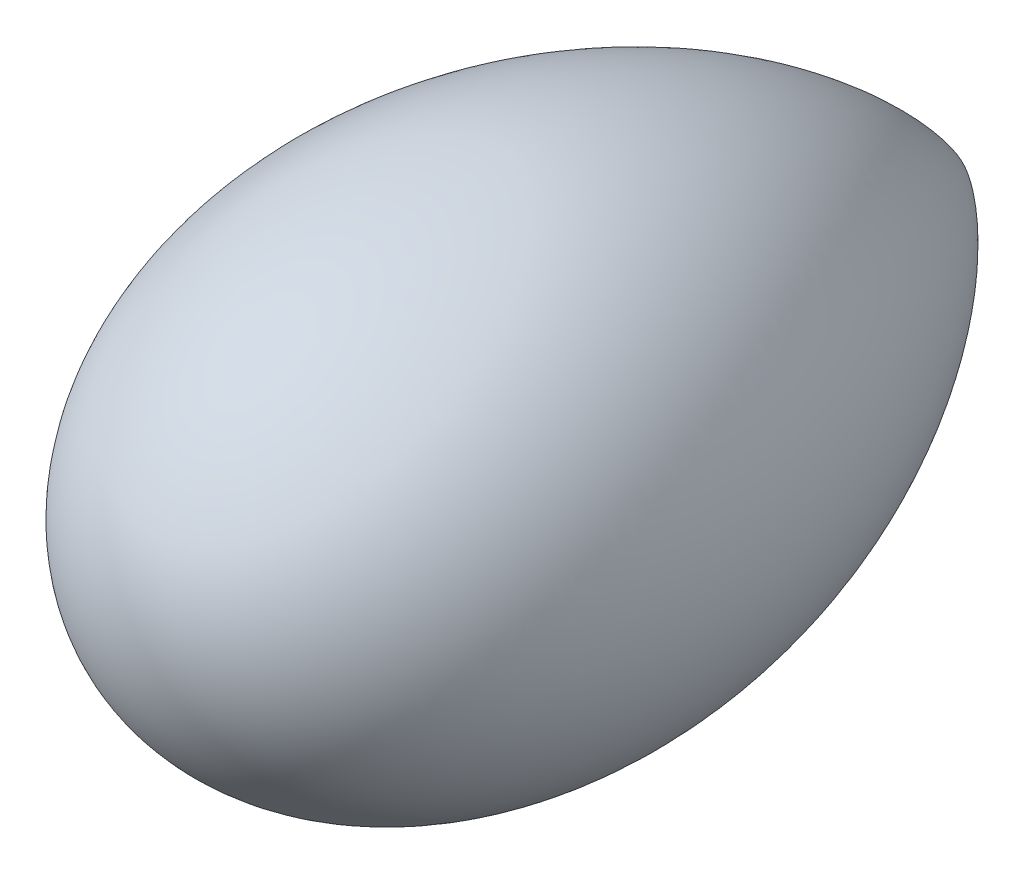
SolidWorks part; units mm, degrees
ref_plane "Front Plane" through (0, 0, 0) normal (0, 0, 1) x (1, 0, 0)
ref_plane "Top Plane" through (0, 0, 0) normal (0, 1, 0) x (1, 0, 0)
ref_plane "Right Plane" through (0, 0, 0) normal (1, 0, 0) x (0, 0, -1)
sketch "Sketch1" plane through (0, 0, 0) normal (0, 1, 0) x (1, 0, 0)
  line L0 (0, 0) -> (0, -55.7313) construction
  line L1 (0, -111.4626) -> (0, 0)
  spline S0 degree 4 poles (-12.5087, -108.2668) (-12.266, -108.3959) (-11.7775, -108.648) (-11.035, -109.0075) (-10.0274, -109.4481) (-9.0074, -109.8468) (-7.977, -110.2028) (-6.9374, -110.5156) (-5.8912, -110.7847) (-4.9658, -110.9822) (-4.169, -111.124) (-3.4992, -111.2236) (-2.9671, -111.292) (-2.4225, -111.3491) (-1.8981, -111.3948) (-1.3334, -111.4292) (-0.841, -111.4521) (-0.2181, -111.4635) (0.2032, -111.4636) (0.8134, -111.4527) (1.292, -111.4312) (1.7718, -111.403) (2.1542, -111.3721) (2.5474, -111.3359) (2.9371, -111.2944) (3.3917, -111.2382) (4.0392, -111.1447) (4.8129, -111.0116) (5.7099, -110.826) (6.9798, -110.5099) (8.482, -110.0508) (9.9521, -109.4954) (11.6226, -108.7419) (13.2441, -107.8883) (14.8128, -106.9401) (16.5278, -105.7371) (18.1608, -104.4253) (19.7092, -103.0148) (21.1713, -101.5153) (22.5463, -99.9356) (24.1563, -97.8715) (25.7407, -95.5252) (27.2623, -92.8896) (28.5916, -90.1533) (29.5695, -87.833) (30.5488, -85.1788) (31.4833, -82.1794) (32.3589, -78.6193) (33.259, -73.4603) (33.8043, -67.1946) (33.7131, -59.8531) (32.692, -51.5269) (30.8192, -43.3516) (28.1468, -35.4025) (24.7149, -27.7508) (21.072, -21.3806) (17.5018, -16.2063) (14.2272, -12.121) (11.7755, -9.3964) (9.557, -7.1726) (7.7692, -5.5355) (6.4734, -4.4233) (5.038, -3.2639) (3.8281, -2.3573) (2.7009, -1.5761) (1.6613, -0.9177) (1.0906, -0.5771) (0.5935, -0.299) (0.2568, -0.1232) (0.086, -0.0402) (0, 0) knots 0 0 0 0 0 0.007194 0.014388 0.021582 0.028776 0.035845 0.042913 0.049982 0.05705 0.060585 0.064119 0.067653 0.071188 0.074722 0.078256 0.08179 0.085325 0.088749 0.092172 0.095596 0.09902 0.100732 0.102444 0.105868 0.109292 0.112716 0.119563 0.126411 0.133259 0.146955 0.16065 0.167498 0.181193 0.194889 0.208584 0.22228 0.235976 0.249671 0.263367 0.277062 0.304453 0.323693 0.342933 0.356628 0.370324 0.397715 0.425106 0.452497 0.507279 0.562062 0.616844 0.671626 0.726408 0.78119 0.835973 0.863364 0.890755 0.918146 0.931841 0.945537 0.954184 0.96283 0.980124 0.985093 0.990062 0.995031 0.997515 1 1 1 1 1 construction
  spline S1 degree 4 poles (0, -111.4626) (0.1197, -111.4626) (0.3594, -111.4608) (0.8134, -111.4527) (1.292, -111.4312) (1.7718, -111.403) (2.1542, -111.3721) (2.5474, -111.3359) (2.9371, -111.2944) (3.3917, -111.2382) (4.0392, -111.1447) (4.8129, -111.0116) (5.7099, -110.826) (6.9798, -110.5099) (8.482, -110.0508) (9.9521, -109.4954) (11.6226, -108.7419) (13.2441, -107.8883) (14.8128, -106.9401) (16.5278, -105.7371) (18.1608, -104.4253) (19.7092, -103.0148) (21.1713, -101.5153) (22.5463, -99.9356) (24.1563, -97.8715) (25.7407, -95.5252) (27.2623, -92.8896) (28.5916, -90.1533) (29.5695, -87.833) (30.5488, -85.1788) (31.4833, -82.1794) (32.3589, -78.6193) (33.259, -73.4603) (33.8043, -67.1946) (33.7131, -59.8531) (32.692, -51.5269) (30.8192, -43.3516) (28.1468, -35.4025) (24.7149, -27.7508) (21.072, -21.3806) (17.5018, -16.2063) (14.2272, -12.121) (11.7755, -9.3964) (9.557, -7.1726) (7.7692, -5.5355) (6.4734, -4.4233) (5.038, -3.2639) (3.8281, -2.3573) (2.7009, -1.5761) (1.6613, -0.9177) (1.0906, -0.5771) (0.5935, -0.299) (0.2568, -0.1232) (0.086, -0.0402) (0, 0) knots 0.085325 0.085325 0.085325 0.085325 0.085325 0.088749 0.092172 0.095596 0.09902 0.100732 0.102444 0.105868 0.109292 0.112716 0.119563 0.126411 0.133259 0.146955 0.16065 0.167498 0.181193 0.194889 0.208584 0.22228 0.235976 0.249671 0.263367 0.277062 0.304453 0.323693 0.342933 0.356628 0.370324 0.397715 0.425106 0.452497 0.507279 0.562062 0.616844 0.671626 0.726408 0.78119 0.835973 0.863364 0.890755 0.918146 0.931841 0.945537 0.954184 0.96283 0.980124 0.985093 0.990062 0.995031 0.997515 1 1 1 1 1
revolve "Revolve1" add sketch "Sketch1" angle 360 about L0
